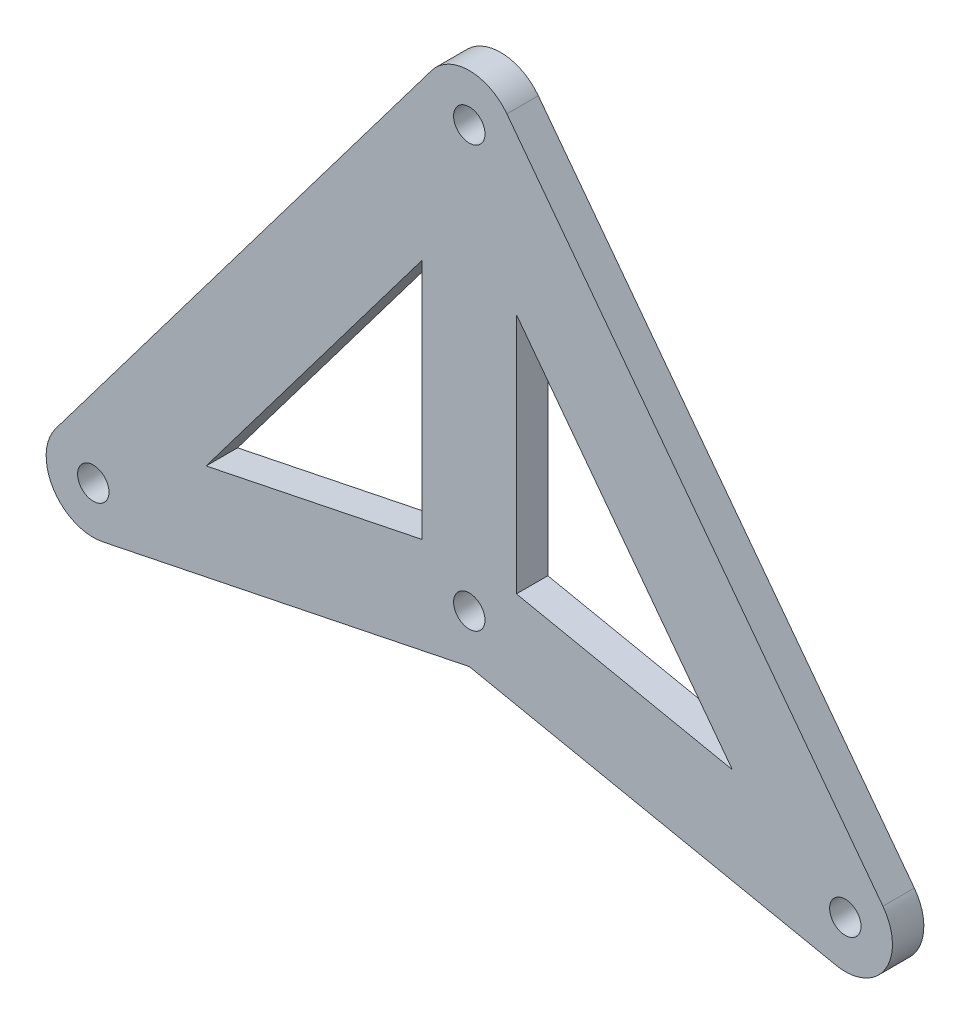
SolidWorks part; units mm, degrees
ref_plane "Front" through (0, 0, 0) normal (0, 0, 1) x (1, 0, 0)
ref_plane "Top" through (0, 0, 0) normal (0, 1, 0) x (1, 0, 0)
ref_plane "Right" through (0, 0, 0) normal (1, 0, 0) x (0, 0, -1)
sketch "Sketch1" plane through (0, 0, 0) normal (0, 0, 1) x (1, 0, 0)
  line L0 (-38, -7.8) -> (0, 0) construction
  line L2 (-37.0424, -12.4652) -> (0, -4.8618)
  line L3 (0, 0) -> (0, 42.545) construction
  line L4 (0, -6.1119) -> (0, 6.1119) construction
  line L5 (-4.7625, 3.8842) -> (-4.7625, 28.33)
  line L6 (4.7625, 3.8842) -> (4.7625, 28.33)
  line L7 (0, 42.545) -> (-38, -7.8) construction
  line L8 (-4.7625, 28.33) -> (-26.5968, -0.5975)
  line L9 (-3.8012, 45.4141) -> (-41.8012, -4.9309)
  line L10 (0, 0) -> (38, -7.8) construction
  line L11 (4.7625, 3.8842) -> (26.5968, -0.5975)
  line L12 (0, -4.8618) -> (37.0424, -12.4652)
  line L13 (38, -7.8) -> (0, 42.545) construction
  line L14 (26.5968, -0.5975) -> (4.7625, 28.33)
  line L15 (41.8012, -4.9309) -> (3.8012, 45.4141)
  line L16 (-38, -7.8) -> (38, -7.8) construction
  line L17 (-26.5968, -0.5975) -> (-4.7625, 3.8842)
  arc A5 (-41.8012, -4.9309) -> (-37.0424, -12.4652) centre (-38, -7.8) ccw
  arc A8 (37.0424, -12.4652) -> (41.8012, -4.9309) centre (38, -7.8) ccw
  arc A9 (3.8012, 45.4141) -> (-3.8012, 45.4141) centre (0, 42.545) ccw
  circle A11 centre (38, -7.8) radius 1.5875
  circle A12 centre (0, 0) radius 1.5875
  circle A13 centre (-38, -7.8) radius 1.5875
  circle A14 centre (0, 42.545) radius 1.5875
  dimension "D3" = 3.175
  dimension "D4" = 4.7625
  dimension "D1" = 9.525
  dimension "D2" = 42.545
extrude "Boss-Extrude2" add sketch "Sketch1" against normal blind 3.175 from offset 4.7625 offset against normal yes
